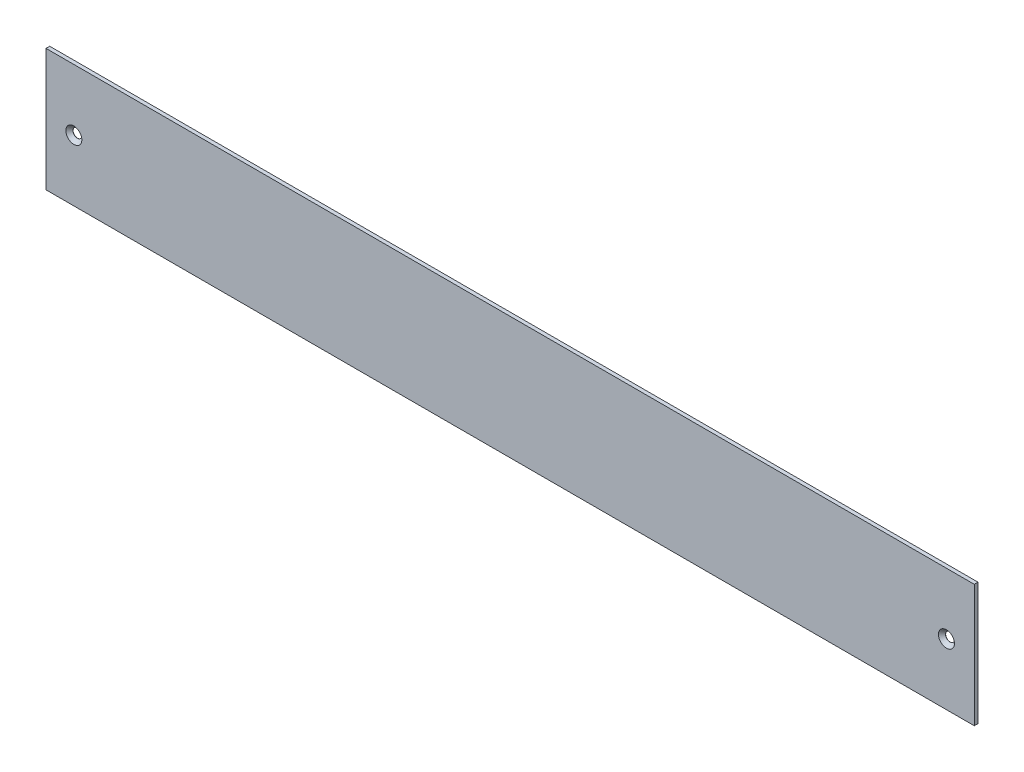
SolidWorks part; units mm, degrees
ref_plane "Ebene vorne" through (0, 0, 0) normal (0, 0, 1) x (1, 0, 0)
ref_plane "Ebene oben" through (0, 0, 0) normal (0, 1, 0) x (1, 0, 0)
ref_plane "Ebene rechts" through (0, 0, 0) normal (1, 0, 0) x (0, 0, -1)
sketch "Skizze1" plane through (0, 0, 0) normal (0, 0, 1) x (1, 0, 0)
  line L0 (-339.9038, 3) -> (160.0962, 3)
  line L1 (160.0962, 3) -> (160.0962, -63)
  line L2 (160.0962, -63) -> (130.0955, -63)
  line L3 (130.0955, -63) -> (130.0955, -71)
  line L5 (130.0955, -71) -> (-309.9038, -71)
  line L6 (-309.9038, -71) -> (-309.9038, -63)
  line L9 (-339.9038, -63) -> (-339.9038, 3)
  line L10 (-339.9038, -63) -> (-309.9038, -63)
  dimension "D1" = 74
  dimension "D2" = 30
  dimension "D3" = 0
extrude "Aufsatz-Linear austragen1" add sketch "Skizze1" along normal blind 2 contours L0 L1 L2 L3 L5 L6 L10 L9
hole_wizard "Formsenkung für M4 Senkschraube mit Innensechskant1" positions "Skizze2" profile "Skizze3" countersink size "M4" standard "DIN" end condition through all
sketch "Skizze2" plane through (0, 0, 2) normal (0, 0, 1) x (1, 0, 0)
  line L0 (-339.9038, -30) -> (160.0962, -30) construction
  line L1 (-339.9038, -63) -> (-339.9038, 3) construction
  line L2 (160.0962, 3) -> (160.0962, -63) construction
  point P11 (-324.9038, -30)
  point P13 (145.0962, -30)
  dimension "D1" = 15
  dimension "D2" = 15
sketch "Skizze3" plane through (145.0962, -30, 2) normal (1, 0, 0) x (0, -1, 0)
  line L0 (0, 0) -> (0, 2)
  line L1 (0, 2) -> (2.4, 2)
  line L2 (2.4, 2) -> (2.4, 1.9)
  line L3 (2.4, 1.9) -> (4.3, 0)
  line L5 (4.3, 0) -> (0, 0)
  line L6 (-2.4, 1.9) -> (-4.3, 0) construction
  line L11 (0, -6.35) -> (0, 107.95) construction
  dimension "Bohrerdurchmesser" = 4.8
  dimension "Bohrungstiefe" = 2
  dimension "Senkdurchmesser (Oben)" = 8.6
  dimension "Senkwinkel (Oben)" = 90
sketch "Skizze4" plane through (0, 0, 2) normal (0, 0, 1) x (1, 0, 0)
  line L0 (160.0962, 3) -> (160.0962, -63) construction
  line L1 (-309.9038, -26) -> (-184.9038, -26)
  line L2 (-309.9038, -26) -> (-309.9038, -34)
  line L3 (-309.9038, -34) -> (-184.9038, -34)
  line L4 (-184.9038, -26) -> (-184.9038, -34)
  line L17 (-174.9038, -26) -> (-44.9038, -26)
  line L18 (-174.9038, -26) -> (-174.9038, -34)
  line L19 (-174.9038, -34) -> (-44.9038, -34)
  line L20 (-44.9038, -26) -> (-44.9038, -34)
  line L25 (-34.9038, -26) -> (130.0962, -26)
  line L26 (-34.9038, -26) -> (-34.9038, -34)
  line L27 (-34.9038, -34) -> (130.0962, -34)
  line L28 (130.0962, -26) -> (130.0962, -34)
  line L33 (-339.9038, 3) -> (160.0962, 3) construction
  line L35 (-339.9038, -63) -> (-339.9038, 3) construction
  dimension "D1" = 30
  dimension "D4" = 8
  dimension "D5" = 29
  dimension "D8" = 10
  dimension "D9" = 29
  dimension "D11" = 8
  dimension "D15" = 10
  dimension "D16" = 29
  dimension "D18" = 30
  dimension "D20" = 8
  dimension "D21" = 195
  dimension "D23" = 130
extrude "Mittelschnitz" [suppressed] cut sketch "Skizze4" against normal blind 10
fillet "Mittelschlitz Verrundung" [suppressed] radius 4
sketch "Skizze5" plane through (0, 0, 0) normal (0, 0, -1) x (-1, 0, 0)
  line L0 (-160.0962, 3) -> (-160.0962, -63) construction
  line L1 (-160.0962, -63) -> (339.9038, -63)
  line L2 (-160.0962, -63) -> (-160.0962, -71)
  line L3 (-160.0962, -71) -> (339.9038, -71)
  line L4 (339.9038, -63) -> (339.9038, -71)
  line L5 (339.9038, -63) -> (339.9038, 3) construction
  line L6 (-130.0955, -71) -> (309.9038, -71) construction
  dimension "D1" = 0
  dimension "D2" = 0
  dimension "D3" = 8
extrude "Schlitz Oben" cut sketch "Skizze5" against normal blind 10
